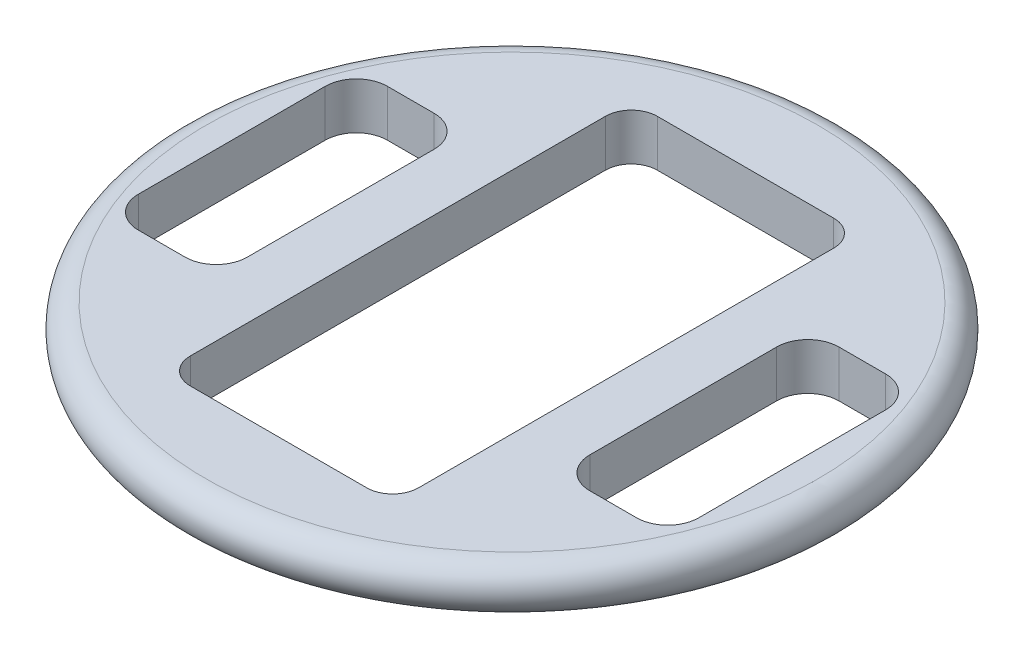
SolidWorks part; units mm, degrees
ref_plane "Front Plane" through (0, 0, 0) normal (0, 0, 1) x (1, 0, 0)
ref_plane "Top Plane" through (0, 0, 0) normal (0, 1, 0) x (1, 0, 0)
ref_plane "Right Plane" through (0, 0, 0) normal (1, 0, 0) x (0, 0, -1)
sketch "Sketch1" plane through (0, 0, 0) normal (0, 1, 0) x (1, 0, 0)
  circle A0 centre (0, 0) radius 29.5
  dimension "D1" = 59
extrude "Boss-Extrude1" add sketch "Sketch1" along normal blind 4.5
sketch "Sketch2" plane through (0, 4.5, 0) normal (0, 1, 0) x (1, 0, 0)
  line L0 (0, -10) -> (0, 10)
  line L1 (-8.5, -22.5) -> (8.5, -22.5)
  line L2 (-11, -20) -> (-11, 20)
  line L3 (-8.5, 22.5) -> (8.5, 22.5)
  line L4 (11, -20) -> (11, 20)
  line L5 (-11, -22.5) -> (11, 22.5) construction
  line L6 (-11, 22.5) -> (11, -22.5) construction
  line L7 (0, 0) -> (-11, 0)
  arc A0 (11, -20) -> (8.5, -22.5) centre (8.5, -20) cw
  arc A1 (-8.5, -22.5) -> (-11, -20) centre (-8.5, -20) cw
  arc A2 (8.5, 22.5) -> (11, 20) centre (8.5, 20) cw
  arc A3 (-11, 20) -> (-8.5, 22.5) centre (-8.5, 20) cw
  point P0 (0, 0)
  point P21 (0, 0)
  dimension "D1" = 2.5
  dimension "D2" = 45
  dimension "D3" = 22
extrude "Cut-Extrude1" cut sketch "Sketch2" against normal through all
sketch "Sketch3" plane through (0, 4.5, 0) normal (0, 1, 0) x (1, 0, 0)
  line L0 (11, 0) -> (-11, 0)
  line L1 (-11, -20) -> (-11, 20) construction
  line L2 (0, -5) -> (0, 5)
  line L3 (-11, 0) -> (-12, 0)
  line L4 (-12, 0) -> (-13.75, 0)
  line L9 (-12, 0) -> (-15.5, 0)
  line L10 (-15.55, -6.05) -> (-11.95, -6.05)
  line L11 (15.55, 6.05) -> (11.95, -6.05) construction
  line L12 (-15.55, -6.05) -> (-15.55, 6.05)
  line L13 (-15.55, 6.05) -> (-11.95, 6.05)
  line L14 (-11.95, -6.05) -> (-11.95, 6.05)
  line L15 (-15.55, -6.05) -> (-11.95, 6.05) construction
  line L16 (-15.55, 6.05) -> (-11.95, -6.05) construction
  line L17 (-15.5, 0) -> (-16.5, 0)
  line L18 (-16.5, 0) -> (-16.5, 9)
  line L19 (-19.5, 12) -> (-24, 12)
  line L20 (-27, 9) -> (-27, -9)
  line L21 (-24, -12) -> (-19.5, -12)
  line L22 (-16.5, -9) -> (-16.5, 0)
  line L23 (15.55, -6.05) -> (11.95, 6.05) construction
  line L24 (16.5, -9) -> (16.5, 0)
  line L25 (24, -12) -> (19.5, -12)
  line L26 (27, 9) -> (27, -9)
  line L27 (19.5, 12) -> (24, 12)
  line L28 (16.5, 0) -> (16.5, 9)
  line L29 (15.5, 0) -> (16.5, 0)
  line L30 (11.95, -6.05) -> (11.95, 6.05)
  line L31 (15.55, 6.05) -> (11.95, 6.05)
  line L32 (15.55, -6.05) -> (15.55, 6.05)
  line L33 (15.55, -6.05) -> (11.95, -6.05)
  line L34 (12, 0) -> (15.5, 0)
  line L35 (12, 0) -> (13.75, 0)
  line L36 (11, 0) -> (12, 0)
  line L37 (0, 0) -> (-29.5, 0) construction
  arc A0 (-16.5, 9) -> (-19.5, 12) centre (-19.5, 9) ccw
  arc A1 (-16.5, -9) -> (-19.5, -12) centre (-19.5, -9) cw
  arc A2 (-24, -12) -> (-27, -9) centre (-24, -9) cw
  arc A3 (-27, 9) -> (-24, 12) centre (-24, 9) cw
  arc A4 (27, 9) -> (24, 12) centre (24, 9) ccw
  arc A5 (24, -12) -> (27, -9) centre (24, -9) ccw
  arc A6 (16.5, -9) -> (19.5, -12) centre (19.5, -9) ccw
  arc A7 (16.5, 9) -> (19.5, 12) centre (19.5, 9) cw
  point P0 (27, 12)
  point P18 (-16.5, 12)
  point P26 (-27, 12)
  point P30 (0, 0)
  point P51 (0, 0)
  point P52 (16.5, 12)
  dimension "D6" = 3
  dimension "D7" = 4.5
  dimension "D1" = 1
  dimension "D2" = 3.5
  dimension "D3" = 1
  dimension "D4" = 10.5
  dimension "D5" = 12
  dimension "D8" = 24
  dimension "D9" = 1.75
extrude "Cut-Extrude2" cut sketch "Sketch3" against normal through all contours A3 L20 A2 L21 A1 L22 L18 A0 L19 | L24 A6 L25 A5 L26 A4 L27 A7 L28
sketch "Sketch4" plane through (0, 0, 0) normal (1, 0, 0) x (0, 0, -1)
  line L0 (29.5, 0) -> (29.5, 4.5) construction
  line L1 (0, 0) -> (0, 9.6209)
  line L2 (29.5, 4.5) -> (29.5, 0)
  circle A0 centre (29.5, 2.25) radius 2.25
  dimension "D1" = 4.5
revolve "Revolve1" add sketch "Sketch4" angle 360 about L1
